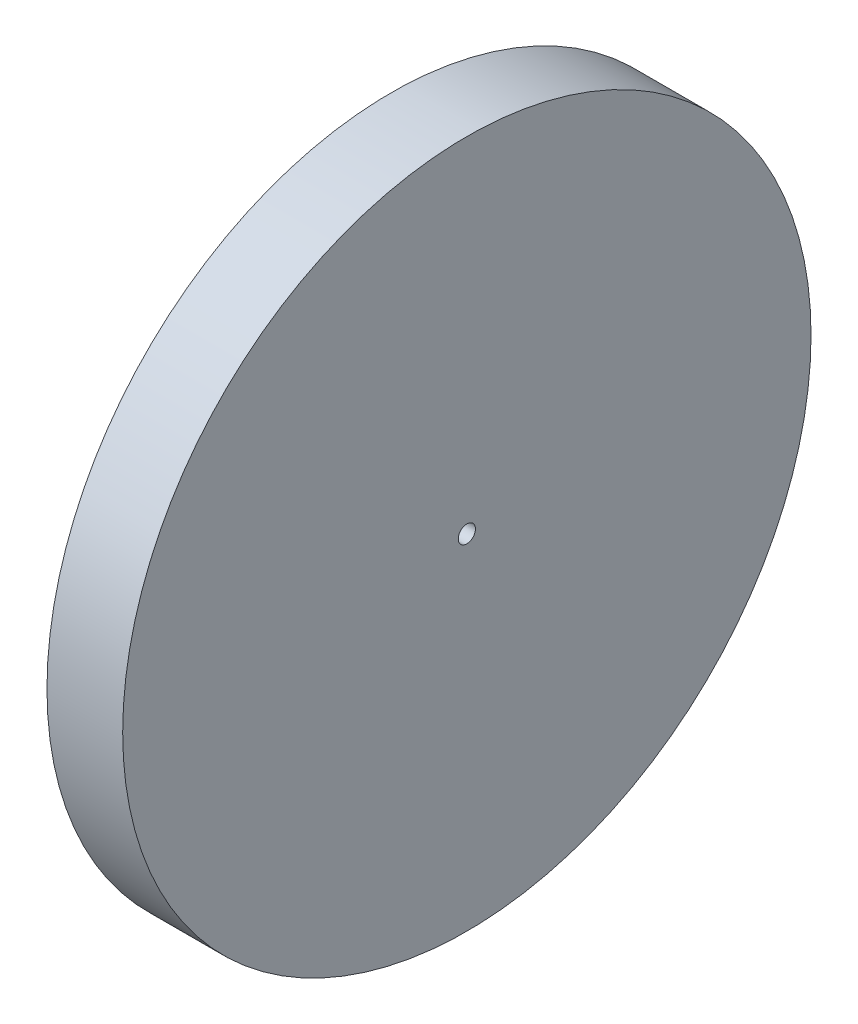
SolidWorks part; units mm, degrees
ref_plane "Plan de face" through (0, 0, 0) normal (0, 0, 1) x (1, 0, 0)
ref_plane "Plan de dessus" through (0, 0, 0) normal (0, 1, 0) x (1, 0, 0)
ref_plane "Plan de droite" through (0, 0, 0) normal (1, 0, 0) x (0, 0, -1)
sketch "Esquisse4" plane through (0, 0, 0) normal (1, 0, 0) x (0, 0, -1)
  circle A0 centre (0, 0) radius 100
extrude "Boss.-Extru.2" add sketch "Esquisse4" along normal blind 22
sketch "Esquisse6" plane through (22, 0, 0) normal (1, 0, 0) x (0, 0, -1)
  circle A0 centre (0, 0) radius 2.5
extrude "Enlèv. mat.-Extru.1" cut sketch "Esquisse6" against normal blind 22
